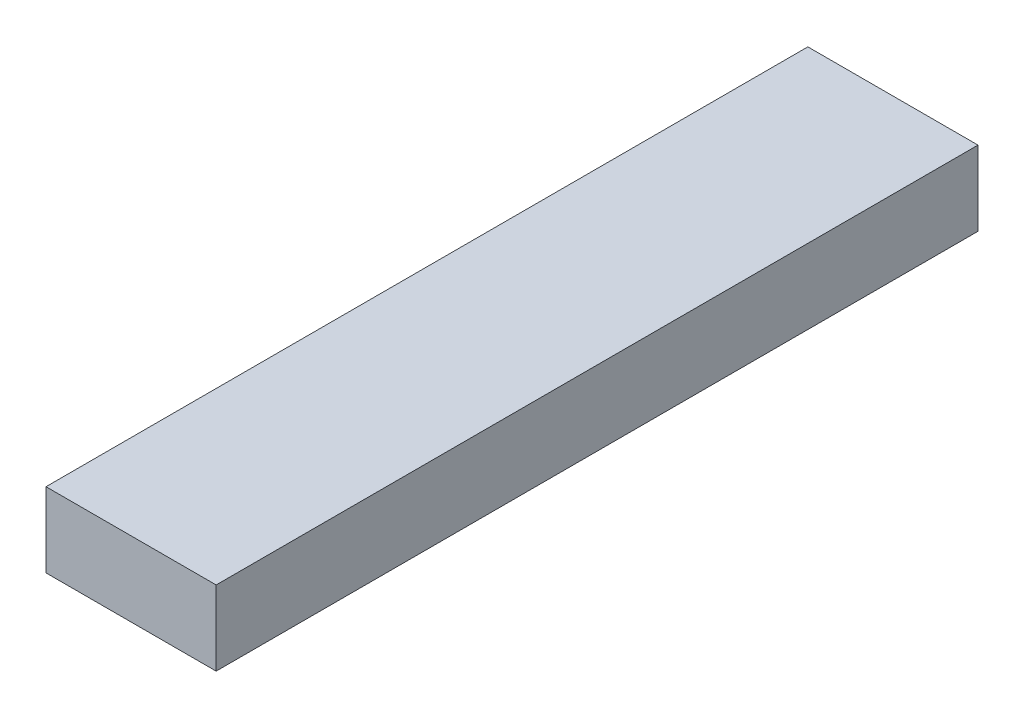
SolidWorks part; units mm, degrees
ref_plane "Front Plane" through (0, 0, 0) normal (0, 0, 1) x (1, 0, 0)
ref_plane "Top Plane" through (0, 0, 0) normal (0, 1, 0) x (1, 0, 0)
ref_plane "Right Plane" through (0, 0, 0) normal (1, 0, 0) x (0, 0, -1)
sketch "Sketch1" plane through (0, 0, 0) normal (0, 0, 1) x (1, 0, 0)
  line L1 (-17.018, -7.4676) -> (17.018, -7.4676)
  line L2 (-17.018, -7.4676) -> (-17.018, 7.4676)
  line L3 (-17.018, 7.4676) -> (17.018, 7.4676)
  line L4 (17.018, -7.4676) -> (17.018, 7.4676)
  line L5 (-17.018, -7.4676) -> (17.018, 7.4676) construction
  line L6 (-17.018, 7.4676) -> (17.018, -7.4676) construction
  point P0 (0, 0)
  dimension "D1" = 34.036
  dimension "D2" = 14.9352
extrude "Boss-Extrude1" add sketch "Sketch1" along normal mid plane 152.4
